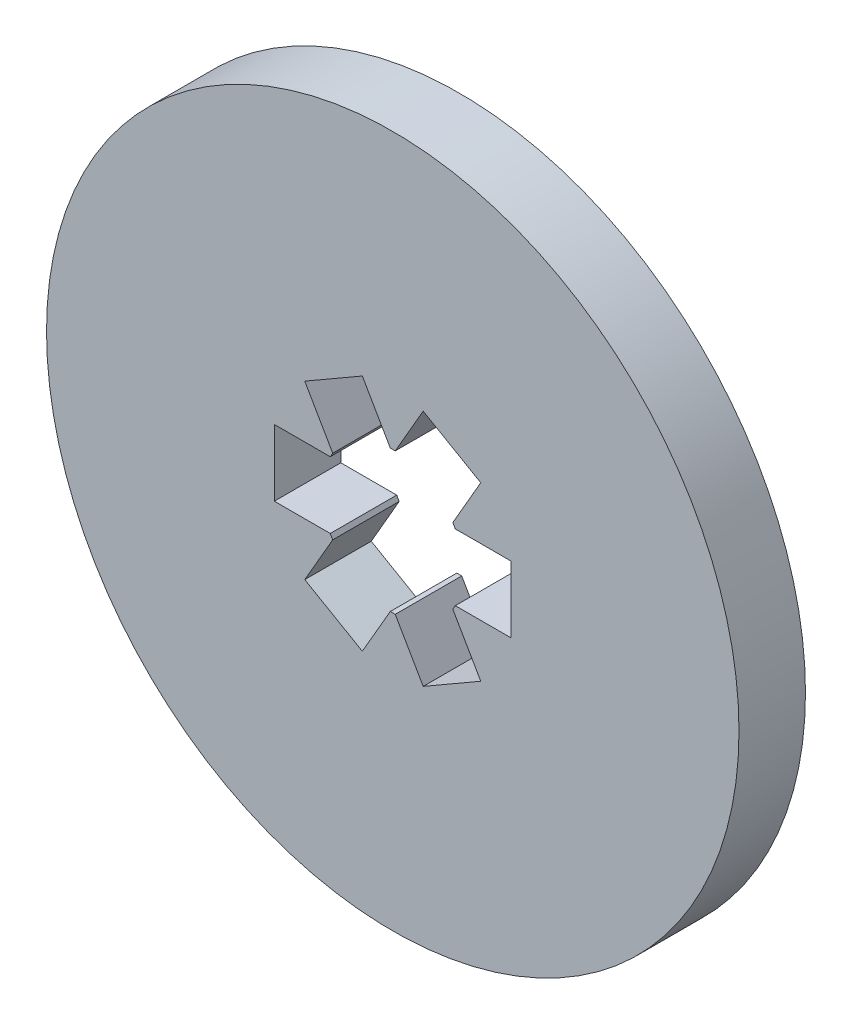
SolidWorks part; units mm, degrees
ref_plane "Front Plane" through (0, 0, 0) normal (0, 0, 1) x (1, 0, 0)
ref_plane "Top Plane" through (0, 0, 0) normal (0, 1, 0) x (1, 0, 0)
ref_plane "Right Plane" through (0, 0, 0) normal (1, 0, 0) x (0, 0, -1)
sketch "Sketch1" plane through (0, 0, 0) normal (0, 0, 1) x (1, 0, 0)
  line L0 (110.2077, 0) -> (110.2077, -1.524)
  line L1 (110.2077, -1.524) -> (108.9259, -1.524)
  line L2 (108.9259, -1.524) -> (108.8691, -1.6222)
  line L3 (108.8691, -1.6222) -> (109.51, -2.7323)
  line L4 (109.51, -2.7323) -> (108.1902, -3.4943)
  line L5 (108.1902, -3.4943) -> (107.5493, -2.3842)
  line L6 (107.5493, -2.3842) -> (107.4359, -2.3842)
  line L7 (107.4359, -2.3842) -> (106.795, -3.4943)
  line L8 (106.795, -3.4943) -> (105.4751, -2.7323)
  line L9 (105.4751, -2.7323) -> (106.116, -1.6222)
  line L10 (106.116, -1.6222) -> (106.0593, -1.524)
  line L11 (106.0593, -1.524) -> (104.7775, -1.524)
  line L12 (104.7775, -1.524) -> (104.7775, 0)
  line L13 (104.7775, 0) -> (106.0593, 0)
  line L14 (106.0593, 0) -> (106.116, 0.0982)
  line L15 (106.116, 0.0982) -> (105.4751, 1.2083)
  line L16 (105.4751, 1.2083) -> (106.795, 1.9703)
  line L17 (106.795, 1.9703) -> (107.4359, 0.8602)
  line L18 (107.4359, 0.8602) -> (107.5493, 0.8602)
  line L19 (107.5493, 0.8602) -> (108.1902, 1.9703)
  line L20 (108.1902, 1.9703) -> (109.51, 1.2083)
  line L21 (109.51, 1.2083) -> (108.8691, 0.0982)
  line L23 (108.8691, 0.0982) -> (108.9259, 0)
  line L24 (108.9259, 0) -> (110.2077, 0)
  circle A0 centre (107.4926, -0.762) radius 7.9375
  dimension "D1" = 15.875
extrude "Boss-Extrude1" add sketch "Sketch1" along normal blind 1.524
